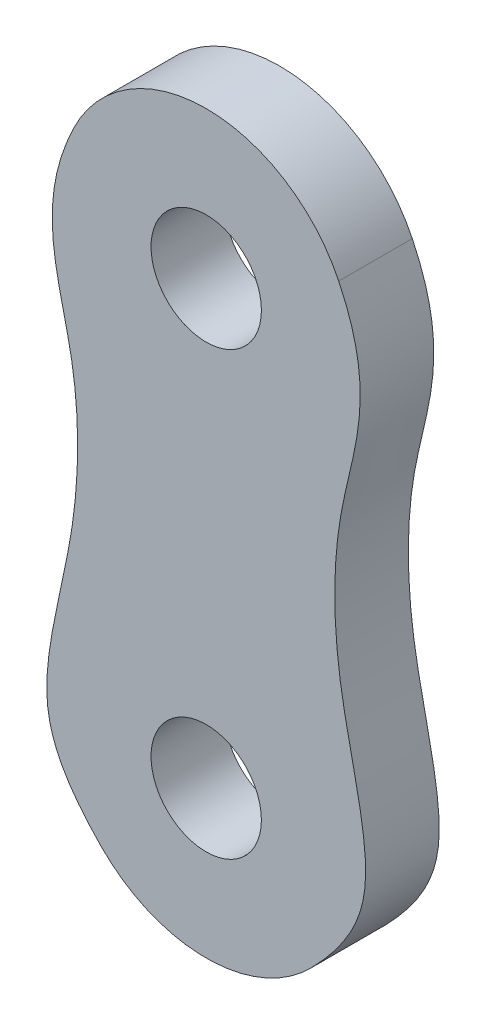
SolidWorks part; units mm, degrees
ref_plane "Front Plane" through (0, 0, 0) normal (0, 0, 1) x (1, 0, 0)
ref_plane "Top Plane" through (0, 0, 0) normal (0, 1, 0) x (1, 0, 0)
ref_plane "Right Plane" through (0, 0, 0) normal (1, 0, 0) x (0, 0, -1)
sketch "Sketch1" plane through (0, 0, 0) normal (0, 0, 1) x (1, 0, 0)
  line L0 (0, 0) -> (0, 3.7939)
  circle A0 centre (0, 0) radius 2.3813
  circle A1 centre (0, 19.05) radius 2.3812
  circle A2 centre (0, 19.05) radius 6.35
  circle A3 centre (0, 0) radius 6.35
  spline S0 degree 3 poles (-5.7186, 21.8105) (-7.4605, 18.2021) (-5.4374, 14.1114) (-5.4747, 6.8833) (-7.3386, 0.6495) (-6.6192, -2.3099) (-4.5438, -4.4358) knots 0 0 0 0 0.323131 0.562945 0.783928 1 1 1 1
  spline S1 degree 3 poles (5.7186, 21.8105) (7.4605, 18.2021) (5.4374, 14.1114) (5.4747, 6.8833) (7.3386, 0.6495) (6.6192, -2.3099) (4.5438, -4.4358) knots 0 0 0 0 0.323131 0.562945 0.783928 1 1 1 1
  dimension "D1" = 4.7625
  dimension "D2" = 4.7625
  dimension "D3" = 19.05
  dimension "D4" = 12.7
  dimension "D5" = 12.7
extrude "Boss-Extrude1" add sketch "Sketch1" along normal blind 3.175
